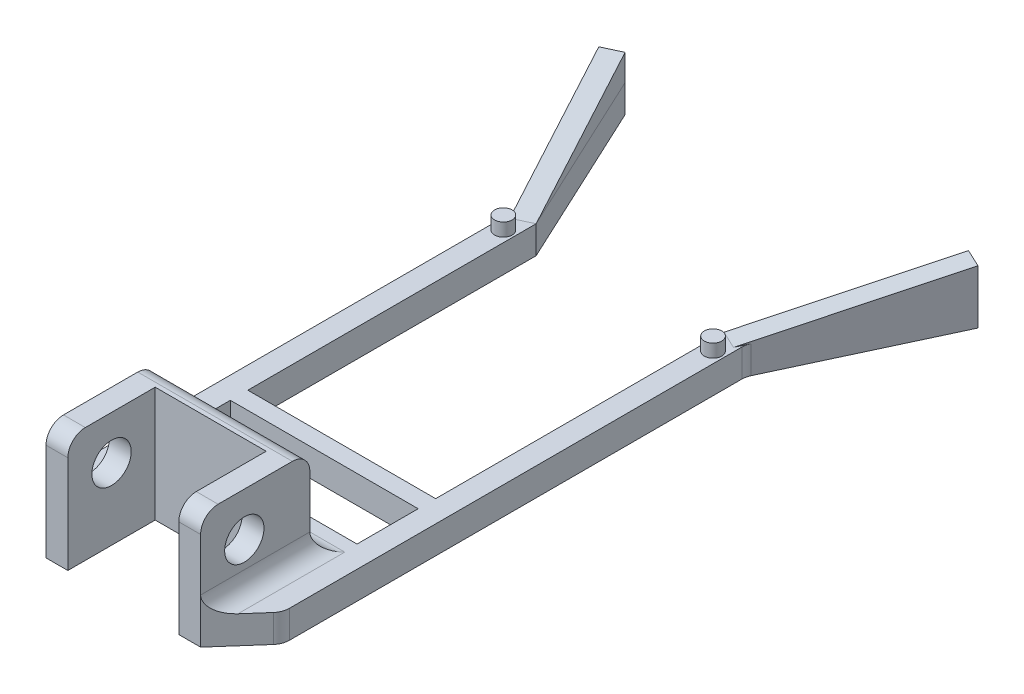
SolidWorks part; units mm, degrees
material "PLA 20%"
ref_plane "Front Plane" through (0, 0, 0) normal (0, 0, 1) x (1, 0, 0)
ref_plane "Top Plane" through (0, 0, 0) normal (0, 1, 0) x (1, 0, 0)
ref_plane "Right Plane" through (0, 0, 0) normal (1, 0, 0) x (0, 0, -1)
sketch "Sketch1" plane through (0, 0, 0) normal (0, 1, 0) x (1, 0, 0)
  line L0 (0, -55) -> (0, 55) construction
  line L12 (10.75, 0) -> (10.75, 33)
  line L15 (-10.75, 0) -> (-10.75, 33)
  line L16 (-10.75, 0) -> (10.75, 0)
  line L17 (-13.25, 33) -> (-13.25, -20)
  line L18 (13.25, -20) -> (13.25, 33)
  line L19 (-10.75, 33) -> (-19.6489, 52.0837)
  line L20 (-19.6489, 52.0837) -> (-21.7024, 51.1262)
  line L21 (-21.7024, 51.1262) -> (-13.25, 33)
  line L22 (19.6489, 52.0837) -> (21.7024, 51.1262)
  line L23 (21.7024, 51.1262) -> (13.25, 33)
  line L24 (10.75, 33) -> (19.6489, 52.0837)
  line L25 (6.35, -15) -> (6.35, -25)
  line L26 (6.35, -25) -> (8.85, -25)
  line L29 (-6.35, -15) -> (-6.35, -25)
  line L30 (-6.35, -25) -> (-8.85, -25)
  line L32 (-6.35, -15) -> (6.35, -15)
  line L33 (8.85, -25) -> (13.25, -20)
  line L34 (-13.25, -20) -> (-8.85, -25)
  line L36 (-10.75, -2) -> (10.75, -2)
  line L37 (-10.75, -2) -> (-10.75, -9)
  line L38 (-10.75, -9) -> (10.75, -9)
  line L39 (10.75, -2) -> (10.75, -9)
  point P0 (0, 0)
  point P23 (6.35, -20)
  dimension "D1" = 21.5
  dimension "D2" = 12.7
  dimension "D3" = 2.5
  dimension "D4" = 20
  dimension "D5" = 155
  dimension "D6" = 58
  dimension "D7" = 2.5
  dimension "D8" = 10
  dimension "D9" = 15
  dimension "D10" = 2
  dimension "D11" = 6
extrude "Boss-Extrude1" add sketch "Sketch1" along normal blind 3.175
sketch "Sketch5" plane through (0, 3.175, 0) normal (0, 1, 0) x (1, 0, 0)
  line L1 (10.75, 33) -> (13.25, 33) construction
  line L2 (10.75, 33) -> (10.75, 0) construction
  line L3 (13.25, -20) -> (13.25, 33) construction
  circle A0 centre (12, 30.5) radius 1
  point P8 (12, 33)
  dimension "D1" = 2
  dimension "D2" = 2.5
extrude "Boss-Extrude4" add sketch "Sketch5" along normal blind 1.5
sketch "Sketch2" plane through (3.8097, 0, -1.7765) normal (0.9063, 0, -0.4226) x (-0.4226, 0, -0.9063)
  line L0 (34.4513, 3.175) -> (55.5078, 6.175)
  line L1 (55.5078, 6.175) -> (55.5078, 3.175)
  line L2 (34.4513, 3.175) -> (55.5078, 3.175) construction
  line L3 (34.4513, 3.175) -> (55.5078, 3.175)
  dimension "D1" = 3
extrude "Boss-Extrude2" add sketch "Sketch2" against normal up to surface (2.2658 mm away) separate body up to face at (-17.4762, 1.5875, -42.0631)
mirror "Mirror4" about plane through (0, 0, 0) normal (1, 0, 0) of "Boss-Extrude4", "Boss-Extrude2"
sketch "Sketch3" plane through (0, 3.175, 0) normal (0, 1, 0) x (1, 0, 0)
  line L0 (-6.35, -15) -> (6.35, -15) construction
  line L7 (-6.35, -15) -> (6.35, -15)
  line L9 (-8.85, -15) -> (-8.85, -12.5)
  line L11 (-8.85, -12.5) -> (8.85, -12.5)
  line L22 (8.85, -15) -> (8.85, -12.5)
  line L23 (6.35, -25) -> (8.85, -25) construction
  line L24 (8.85, -25) -> (6.35, -25)
  line L25 (8.85, -25) -> (8.85, -15)
  line L27 (6.35, -25) -> (6.35, -15)
  line L28 (6.35, -15) -> (6.35, -25) construction
  line L29 (0, -55) -> (0, 55) construction
  line L31 (-6.35, -25) -> (-6.35, -15)
  line L32 (-8.85, -25) -> (-6.35, -25)
  line L33 (-8.85, -25) -> (-8.85, -15)
  line L34 (-13.25, -20) -> (-8.85, -25) construction
  line L35 (-8.85, -25) -> (-6.35, -25) construction
extrude "Boss-Extrude3" add sketch "Sketch3" along normal blind 10
sketch "Sketch4" plane through (8.85, 0, 0) normal (1, 0, 0) x (0, 0, -1)
  line L2 (-25, 13.175) -> (-25, 3.175) construction
  line L3 (-15, 3.175) -> (-25, 3.175) construction
  circle A0 centre (-20, 8.175) radius 2.25
  point P11 (-25, 8.175)
  point P12 (-20, 3.175)
  dimension "D1" = 4.5
extrude "Cut-Extrude1" cut sketch "Sketch4" against normal through all
fillet "Fillet1" radius 2 10 edges at (-8.85, 3.175, 18.75) (8.85, 3.175, 18.75) (13.25, 1.5875, -33) (13.25, 1.5875, 20) (-13.25, 1.5875, -33) (-13.25, 1.5875, 20) (7.6, 13.175, 25) (-7.6, 13.175, 25) (0, 13.175, 12.5) (0, 3.175, 12.5)
